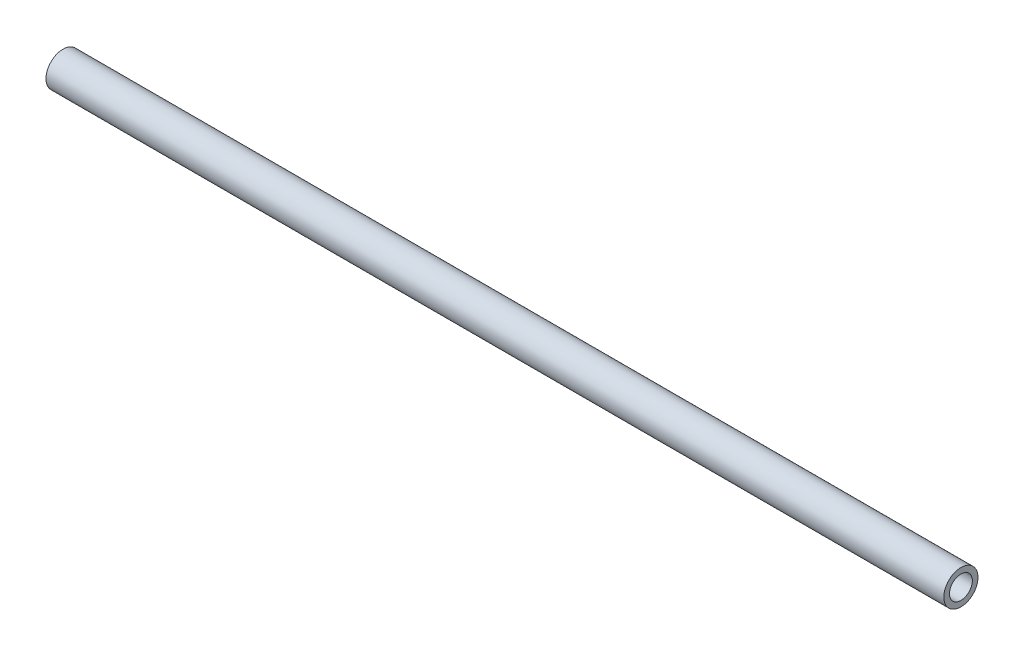
SolidWorks part; units mm, degrees
ref_plane "Front Plane" through (0, 0, 0) normal (0, 0, 1) x (1, 0, 0)
ref_plane "Top Plane" through (0, 0, 0) normal (0, 1, 0) x (1, 0, 0)
ref_plane "Right Plane" through (0, 0, 0) normal (1, 0, 0) x (0, 0, -1)
sketch "Sketch1" plane through (0, 0, 0) normal (1, 0, 0) x (0, 0, -1)
  circle A0 centre (0, 0) radius 1.4986
  circle A1 centre (0, 0) radius 1.0033
  dimension "D1" = 2.9972
  dimension "D2" = 2.0066
extrude "Boss-Extrude1" add sketch "Sketch1" along normal mid plane 78.74
